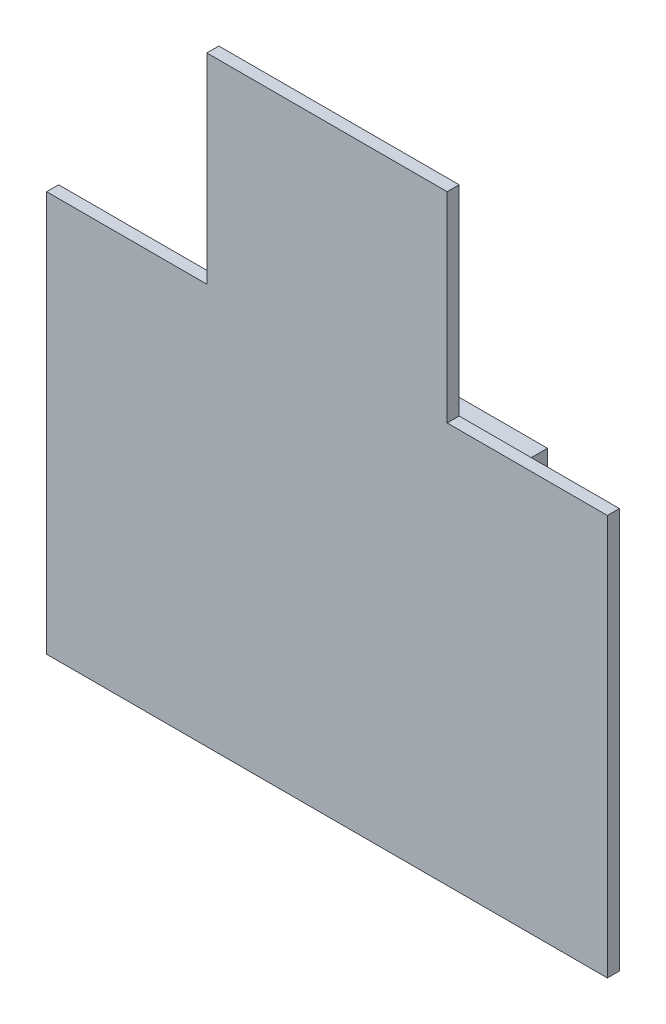
SolidWorks part; units mm, degrees
ref_plane "前视基准面" through (0, 0, 0) normal (0, 0, 1) x (1, 0, 0)
ref_plane "上视基准面" through (0, 0, 0) normal (0, 1, 0) x (1, 0, 0)
ref_plane "右视基准面" through (0, 0, 0) normal (1, 0, 0) x (0, 0, -1)
sketch "草图1" plane through (0, 0, 0) normal (0, 0, 1) x (1, 0, 0)
  line L1 (-70, -50) -> (70, -50)
  line L2 (-70, -50) -> (-70, 50)
  line L3 (-70, 50) -> (70, 50)
  line L4 (70, -50) -> (70, 50)
  line L5 (-70, -50) -> (70, 50) construction
  line L6 (-70, 50) -> (70, -50) construction
  point P0 (0, 0)
  dimension "D1" = 100
  dimension "D2" = 140
extrude "凸台-拉伸1" add sketch "草图1" along normal blind 3 contours L3 L4 L1 L2
sketch "草图2" plane through (0, 50, 0) normal (0, 1, 0) x (1, 0, 0)
  line L0 (-30, 0) -> (-30, -3)
  line L1 (30, 0) -> (30, -3)
  line L4 (70, 0) -> (-70, 0)
  line L5 (-70, 0) -> (-70, -3)
  line L6 (-70, -3) -> (70, -3)
  line L7 (70, -3) -> (70, 0)
  line L8 (30, 0) -> (-30, 0)
  line L10 (-30, -3) -> (30, -3)
  point P8 (0, -3)
  dimension "D2" = 60
  dimension "D1" = 0
extrude "凸台-拉伸2" add sketch "草图2" along normal blind 50
sketch "草图3" plane through (0, 0, 0) normal (0, 0, -1) x (-1, 0, 0)
  line L1 (32.0376, 34.0531) -> (-32.0376, 34.0531)
  line L2 (32.0376, 34.0531) -> (32.0376, -34.0531)
  line L3 (32.0376, -34.0531) -> (-32.0376, -34.0531)
  line L4 (-32.0376, 34.0531) -> (-32.0376, -34.0531)
  line L5 (32.0376, 34.0531) -> (-32.0376, -34.0531) construction
  line L6 (32.0376, -34.0531) -> (-32.0376, 34.0531) construction
  point P0 (0, 0)
extrude "凸台-拉伸3" add sketch "草图3" along normal blind 20
sketch "草图4" plane through (0, 0, -20) normal (0, 0, -1) x (-1, 0, 0)
  circle A0 centre (17.8742, 0) radius 7.4332
  circle A1 centre (-15.8373, 0) radius 7.4332
extrude "凸台-拉伸4" add sketch "草图4" along normal blind 10
